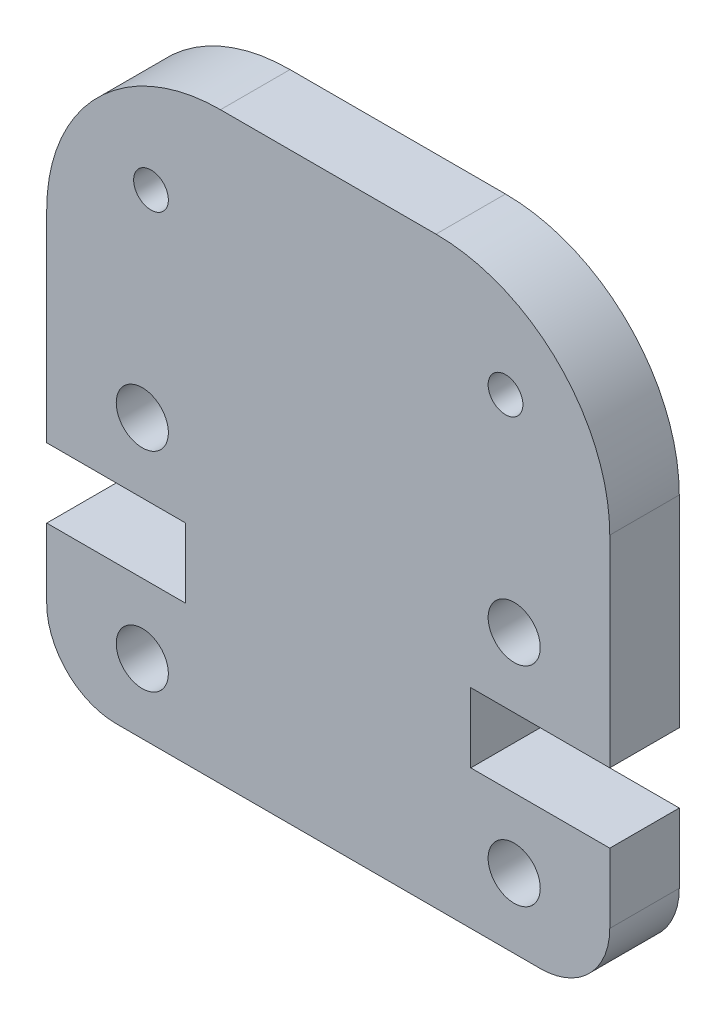
SolidWorks part; units mm, degrees
ref_plane "Front Plane" through (0, 0, 0) normal (0, 0, 1) x (1, 0, 0)
ref_plane "Top Plane" through (0, 0, 0) normal (0, 1, 0) x (1, 0, 0)
ref_plane "Right Plane" through (0, 0, 0) normal (1, 0, 0) x (0, 0, -1)
sketch "Sketch1" plane through (0, 0, 0) normal (0, 0, 1) x (1, 0, 0)
  line L0 (0, 6) -> (0, 11.8)
  line L1 (16.2, 11.8) -> (16.2, 6)
  line L2 (5, 16.8) -> (11.2, 16.8)
  line L3 (2, 0) -> (14.2, 0)
  line L4 (16.2, 2) -> (16.2, 4)
  line L5 (0, 2) -> (0, 4)
  line L6 (0, 6) -> (4, 6)
  line L7 (12.2, 4) -> (16.2, 4)
  line L8 (4, 6) -> (4, 4)
  line L9 (4, 4) -> (0, 4)
  line L10 (12.2, 6) -> (12.2, 4)
  line L11 (16.2, 6) -> (12.2, 6)
  arc A0 (14.2, 0) -> (16.2, 2) centre (14.2, 2) ccw
  arc A1 (5, 16.8) -> (0, 11.8) centre (5, 11.8) ccw
  arc A2 (16.2, 11.8) -> (11.2, 16.8) centre (11.2, 11.8) ccw
  circle A3 centre (3, 13.8) radius 0.5
  circle A4 centre (13.2, 13.8) radius 0.5
  arc A5 (0, 2) -> (2, 0) centre (2, 2) ccw
  circle A6 centre (13.45, 8) radius 0.75
  circle A7 centre (2.75, 8) radius 0.75
  circle A8 centre (13.45, 2) radius 0.75
  circle A9 centre (2.75, 2) radius 0.75
extrude "Boss-Extrude1" add sketch "Sketch1" along normal blind 2
